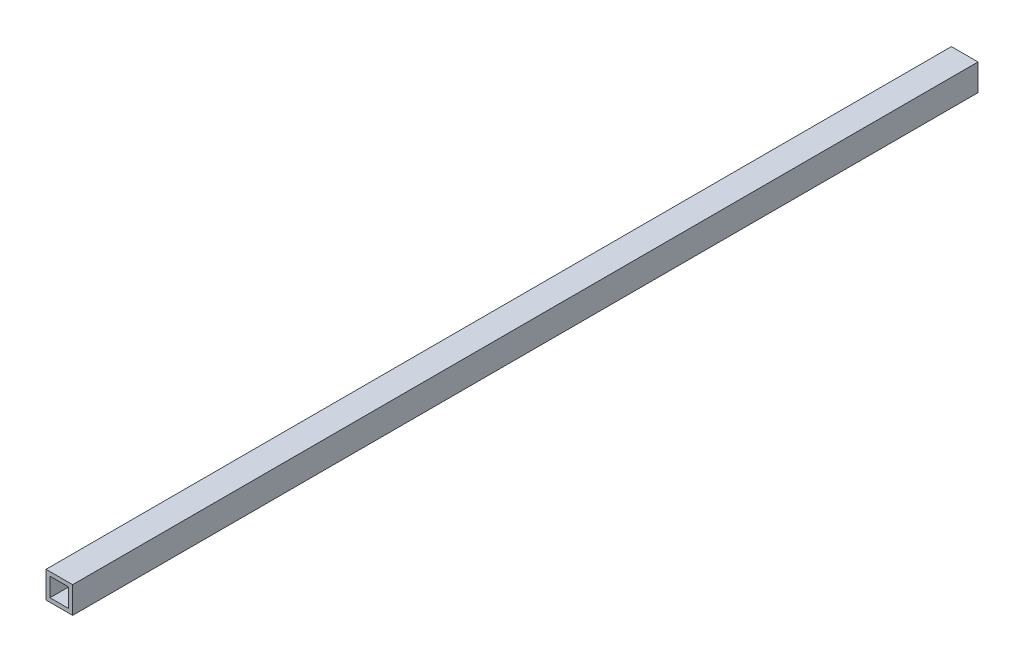
SolidWorks part; units mm, degrees
ref_plane "Płaszczyzna przednia" through (0, 0, 0) normal (0, 0, 1) x (1, 0, 0)
ref_plane "Płaszczyzna górna" through (0, 0, 0) normal (0, 1, 0) x (1, 0, 0)
ref_plane "Płaszczyzna prawa" through (0, 0, 0) normal (1, 0, 0) x (0, 0, -1)
sketch "Szkic1" plane through (0, 0, 0) normal (0, 0, 1) x (1, 0, 0)
  line L1 (-3.5, -3.5) -> (3.5, -3.5)
  line L2 (-3.5, -3.5) -> (-3.5, 3.5)
  line L3 (-3.5, 3.5) -> (3.5, 3.5)
  line L4 (3.5, -3.5) -> (3.5, 3.5)
  line L5 (-3.5, -3.5) -> (3.5, 3.5) construction
  line L6 (-3.5, 3.5) -> (3.5, -3.5) construction
  line L7 (-5, -5) -> (5, -5)
  line L8 (-5, -5) -> (-5, 5)
  line L9 (-5, 5) -> (5, 5)
  line L10 (5, -5) -> (5, 5)
  line L11 (-5, -5) -> (5, 5) construction
  line L12 (-5, 5) -> (5, -5) construction
  point P0 (0, 0)
  point P5 (0, 0)
  dimension "D1" = 7
  dimension "D2" = 10
extrude "Dodanie-wyciągnięcie1" add sketch "Szkic1" along normal blind 340
